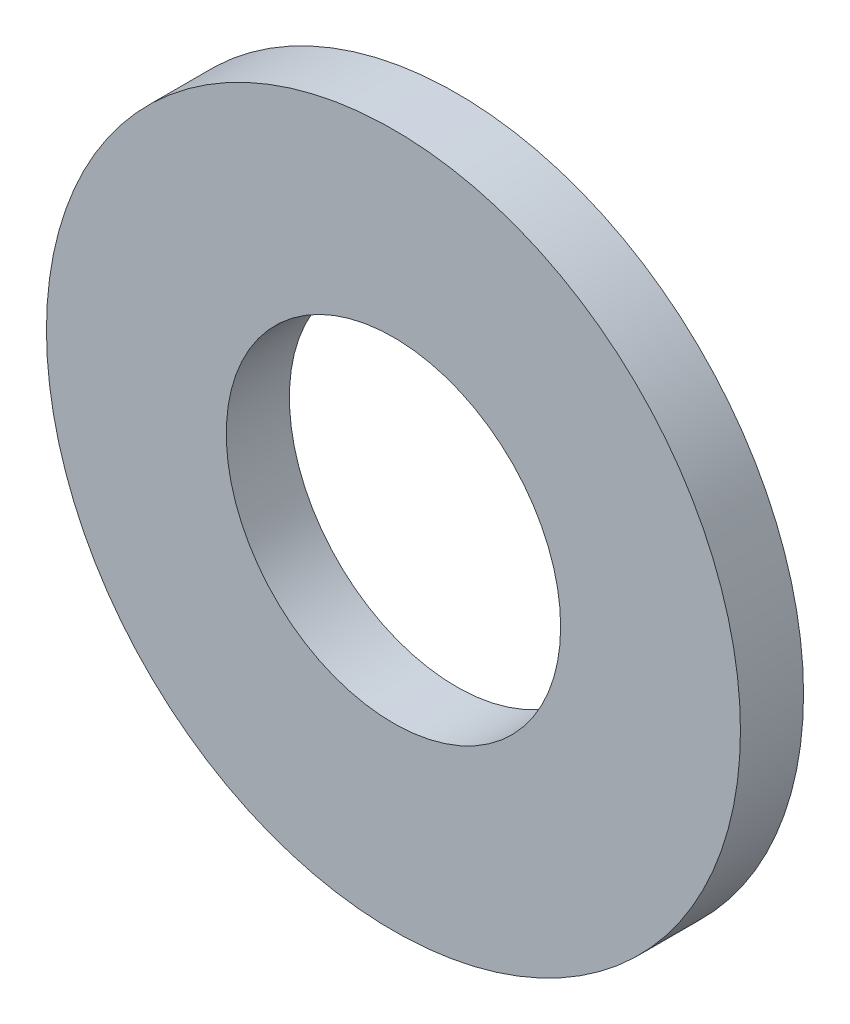
SolidWorks part; units mm, degrees
ref_plane "Front Plane" through (0, 0, 0) normal (0, 0, 1) x (1, 0, 0)
ref_plane "Top Plane" through (0, 0, 0) normal (0, 1, 0) x (1, 0, 0)
ref_plane "Right Plane" through (0, 0, 0) normal (1, 0, 0) x (0, 0, -1)
sketch "Sketch1" plane through (0, 0, 0) normal (0, 0, 1) x (1, 0, 0)
  circle A0 centre (0, 0) radius 2.65
  circle A1 centre (0, 0) radius 5.5
  dimension "D1" = 5.3
  dimension "D2" = 11
extrude "Boss-Extrude1" add sketch "Sketch1" along normal blind 1
